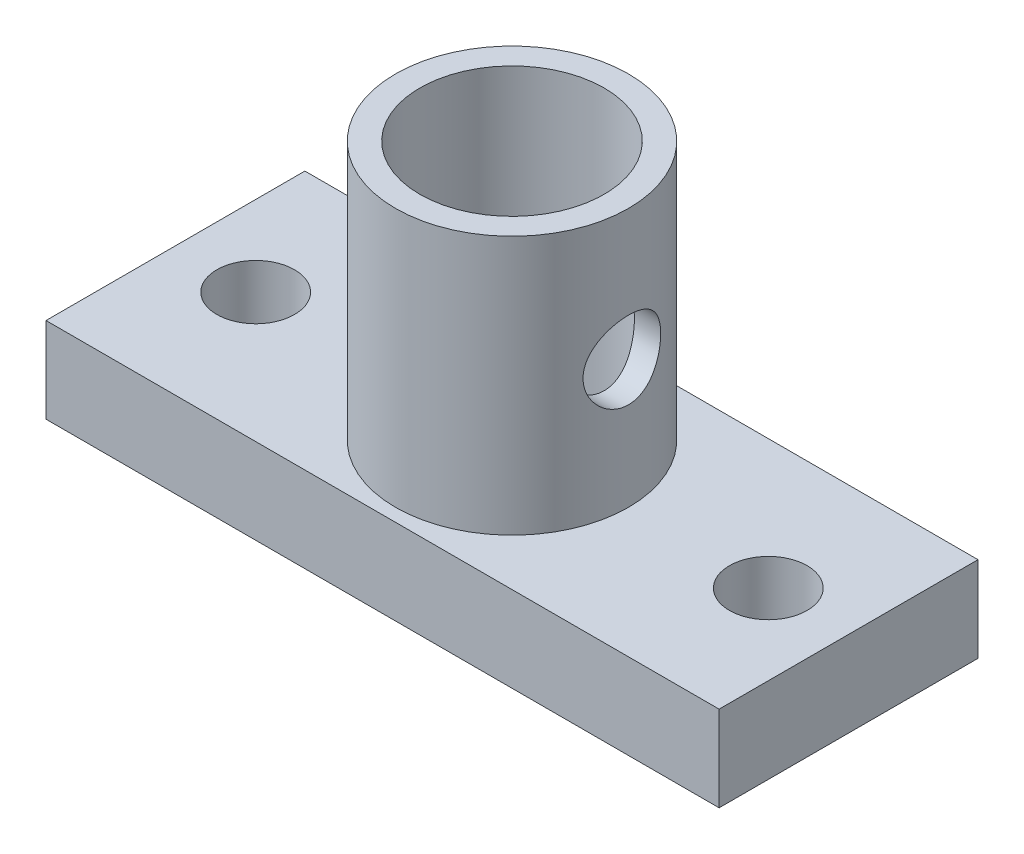
SolidWorks part; units mm, degrees
material "ABS"
ref_plane "Front Plane" through (0, 0, 0) normal (0, 0, 1) x (1, 0, 0)
ref_plane "Top Plane" through (0, 0, 0) normal (0, 1, 0) x (1, 0, 0)
ref_plane "Right Plane" through (0, 0, 0) normal (1, 0, 0) x (0, 0, -1)
sketch "Sketch1" plane through (0, 0, 0) normal (0, 1, 0) x (1, 0, 0)
  line L1 (-13, -5) -> (13, -5)
  line L2 (-13, -5) -> (-13, 5)
  line L3 (-13, 5) -> (13, 5)
  line L4 (13, -5) -> (13, 5)
  line L5 (-13, -5) -> (13, 5) construction
  line L6 (-13, 5) -> (13, -5) construction
  circle A0 centre (-9.9, 0) radius 1.5
  circle A1 centre (9.9, 0) radius 1.5
  point P0 (0, 0)
  dimension "D2" = 3
  dimension "D1" = 26
  dimension "D3" = 19.8
  dimension "D4" = 9.9
  dimension "D5" = 10
extrude "Boss-Extrude5" add sketch "Sketch1" along normal blind 3.302
sketch "Sketch5" plane through (0, 3.302, 0) normal (0, 1, 0) x (1, 0, 0)
  circle A0 centre (0, 0) radius 3.56
  circle A1 centre (0, 0) radius 4.5
  circle A2 centre (-9.9, 0) radius 1.5 construction
  dimension "D1" = 7.12
  dimension "D2" = 9
extrude "Boss-Extrude7" add sketch "Sketch5" along normal blind 10
sketch "Sketch7" plane through (0, 0, 0) normal (1, 0, 0) x (0, 0, -1)
  circle A0 centre (0, 8.2327) radius 1.5
  dimension "D1" = 3
  dimension "D2" = 8.2327
extrude "Cut-Extrude1" cut sketch "Sketch7" along normal blind 10
sketch "Croquis1" plane through (0, 3.302, 0) normal (0, 1, 0) x (1, 0, 0)
  circle A1 centre (0, 0) radius 3.56
  circle A2 centre (0, 0) radius 3.56
  dimension "D1" = 0
extrude "Cortar-Extruir1" cut sketch "Croquis1" against normal blind 10
